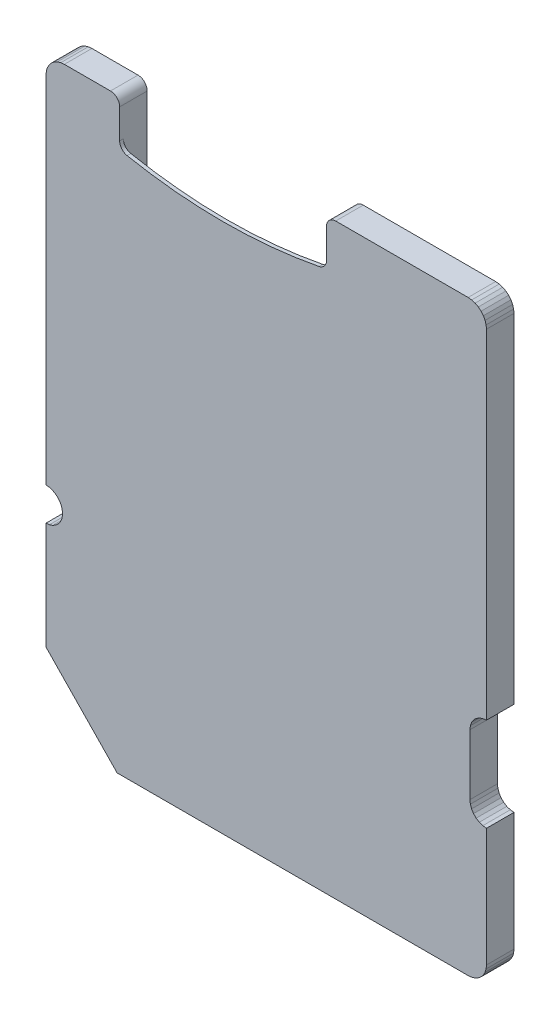
SolidWorks part; units mm, degrees
ref_plane "Ebene vorne" through (0, 0, 0) normal (0, 0, 1) x (1, 0, 0)
ref_plane "Ebene oben" through (0, 0, 0) normal (0, 1, 0) x (1, 0, 0)
ref_plane "Ebene rechts" through (0, 0, 0) normal (1, 0, 0) x (0, 0, -1)
sketch "Skizze1" plane through (0, 0, 0) normal (0, 0, 1) x (1, 0, 0)
  line L201 (121.9951, -56.6192) -> (121.8, -56.6)
  line L202 (121.8, -56.6) -> (99.8, -56.6)
  line L203 (99.8, -56.6) -> (99.6049, -56.6192)
  line L204 (99.6049, -56.6192) -> (99.4173, -56.6761)
  line L205 (99.4173, -56.6761) -> (99.2444, -56.7685)
  line L206 (99.2444, -56.7685) -> (99.0929, -56.8929)
  line L207 (99.0929, -56.8929) -> (98.9685, -57.0444)
  line L208 (98.9685, -57.0444) -> (98.8761, -57.2173)
  line L209 (98.8761, -57.2173) -> (98.8192, -57.4049)
  line L210 (98.8192, -57.4049) -> (98.8, -57.6)
  line L211 (98.8, -57.6) -> (98.8, -76.95)
  line L212 (98.8, -76.95) -> (98.9871, -76.9697)
  line L213 (98.9871, -76.9697) -> (99.1661, -77.0278)
  line L214 (99.1661, -77.0278) -> (99.329, -77.1219)
  line L215 (99.329, -77.1219) -> (99.4688, -77.2478)
  line L216 (99.4688, -77.2478) -> (99.5794, -77.4)
  line L217 (99.5794, -77.4) -> (99.656, -77.5719)
  line L218 (99.656, -77.5719) -> (99.6951, -77.7559)
  line L219 (99.6951, -77.7559) -> (99.6951, -77.9441)
  line L220 (99.6951, -77.9441) -> (99.656, -78.1281)
  line L221 (99.656, -78.1281) -> (99.5794, -78.3)
  line L222 (99.5794, -78.3) -> (99.4688, -78.4522)
  line L223 (99.4688, -78.4522) -> (99.329, -78.5781)
  line L224 (99.329, -78.5781) -> (99.1661, -78.6722)
  line L225 (99.1661, -78.6722) -> (98.9871, -78.7303)
  line L226 (98.9871, -78.7303) -> (98.8, -78.75)
  line L227 (98.8, -78.75) -> (98.8, -84.6)
  line L228 (98.8, -84.6) -> (102.675, -88.6)
  line L229 (102.675, -88.6) -> (121.8, -88.6)
  line L230 (121.8, -88.6) -> (121.9951, -88.5808)
  line L231 (121.9951, -88.5808) -> (122.1827, -88.5239)
  line L232 (122.1827, -88.5239) -> (122.3556, -88.4315)
  line L233 (122.3556, -88.4315) -> (122.5071, -88.3071)
  line L234 (122.5071, -88.3071) -> (122.6315, -88.1556)
  line L235 (122.6315, -88.1556) -> (122.7239, -87.9827)
  line L236 (122.7239, -87.9827) -> (122.7808, -87.7951)
  line L237 (122.7808, -87.7951) -> (122.8, -87.6)
  line L238 (122.8, -87.6) -> (122.8, -81.15)
  line L239 (122.8, -81.15) -> (122.5997, -81.1274)
  line L240 (122.5997, -81.1274) -> (122.4095, -81.0609)
  line L241 (122.4095, -81.0609) -> (122.2389, -80.9536)
  line L242 (122.2389, -80.9536) -> (122.0964, -80.8111)
  line L243 (122.0964, -80.8111) -> (121.9891, -80.6405)
  line L244 (121.9891, -80.6405) -> (121.9226, -80.4503)
  line L245 (121.9226, -80.4503) -> (121.9, -80.25)
  line L246 (121.9, -80.25) -> (121.9, -76.95)
  line L247 (121.9, -76.95) -> (121.9226, -76.7497)
  line L248 (121.9226, -76.7497) -> (121.9891, -76.5595)
  line L249 (121.9891, -76.5595) -> (122.0964, -76.3889)
  line L250 (122.0964, -76.3889) -> (122.2389, -76.2464)
  line L251 (122.2389, -76.2464) -> (122.4095, -76.1391)
  line L252 (122.4095, -76.1391) -> (122.5997, -76.0726)
  line L253 (122.5997, -76.0726) -> (122.8, -76.05)
  line L254 (122.8, -76.05) -> (122.8, -57.6)
  line L255 (122.8, -57.6) -> (122.7808, -57.4049)
  line L256 (122.7808, -57.4049) -> (122.7239, -57.2173)
  line L257 (122.7239, -57.2173) -> (122.6315, -57.0444)
  line L258 (122.6315, -57.0444) -> (122.5071, -56.8929)
  line L259 (122.5071, -56.8929) -> (122.3556, -56.7685)
  line L260 (122.3556, -56.7685) -> (122.1827, -56.6761)
  line L261 (122.1827, -56.6761) -> (121.9951, -56.6192)
  line L262 (121.9951, -56.6192) -> (121.8, -56.6)
  line L263 (121.8, -56.6) -> (99.8, -56.6)
  line L264 (99.8, -56.6) -> (99.6049, -56.6192)
  line L265 (99.6049, -56.6192) -> (99.4173, -56.6761)
  line L266 (99.4173, -56.6761) -> (99.2444, -56.7685)
  line L267 (99.2444, -56.7685) -> (99.0929, -56.8929)
  line L268 (99.0929, -56.8929) -> (98.9685, -57.0444)
  line L269 (98.9685, -57.0444) -> (98.8761, -57.2173)
  line L270 (98.8761, -57.2173) -> (98.8192, -57.4049)
  line L271 (98.8192, -57.4049) -> (98.8, -57.6)
  line L272 (98.8, -57.6) -> (98.8, -76.95)
  line L273 (98.8, -76.95) -> (98.9871, -76.9697)
  line L274 (98.9871, -76.9697) -> (99.1661, -77.0278)
  line L275 (99.1661, -77.0278) -> (99.329, -77.1219)
  line L276 (99.329, -77.1219) -> (99.4688, -77.2478)
  line L277 (99.4688, -77.2478) -> (99.5794, -77.4)
  line L278 (99.5794, -77.4) -> (99.656, -77.5719)
  line L279 (99.656, -77.5719) -> (99.6951, -77.7559)
  line L280 (99.6951, -77.7559) -> (99.6951, -77.9441)
  line L281 (99.6951, -77.9441) -> (99.656, -78.1281)
  line L282 (99.656, -78.1281) -> (99.5794, -78.3)
  line L283 (99.5794, -78.3) -> (99.4688, -78.4522)
  line L284 (99.4688, -78.4522) -> (99.329, -78.5781)
  line L285 (99.329, -78.5781) -> (99.1661, -78.6722)
  line L286 (99.1661, -78.6722) -> (98.9871, -78.7303)
  line L287 (98.9871, -78.7303) -> (98.8, -78.75)
  line L288 (98.8, -78.75) -> (98.8, -84.6)
  line L289 (98.8, -84.6) -> (102.675, -88.6)
  line L290 (102.675, -88.6) -> (121.8, -88.6)
  line L291 (121.8, -88.6) -> (121.9951, -88.5808)
  line L292 (121.9951, -88.5808) -> (122.1827, -88.5239)
  line L293 (122.1827, -88.5239) -> (122.3556, -88.4315)
  line L294 (122.3556, -88.4315) -> (122.5071, -88.3071)
  line L295 (122.5071, -88.3071) -> (122.6315, -88.1556)
  line L296 (122.6315, -88.1556) -> (122.7239, -87.9827)
  line L297 (122.7239, -87.9827) -> (122.7808, -87.7951)
  line L298 (122.7808, -87.7951) -> (122.8, -87.6)
  line L299 (122.8, -87.6) -> (122.8, -81.15)
  line L300 (122.8, -81.15) -> (122.5997, -81.1274)
  line L301 (122.5997, -81.1274) -> (122.4095, -81.0609)
  line L302 (122.4095, -81.0609) -> (122.2389, -80.9536)
  line L303 (122.2389, -80.9536) -> (122.0964, -80.8111)
  line L304 (122.0964, -80.8111) -> (121.9891, -80.6405)
  line L305 (121.9891, -80.6405) -> (121.9226, -80.4503)
  line L306 (121.9226, -80.4503) -> (121.9, -80.25)
  line L307 (121.9, -80.25) -> (121.9, -76.95)
  line L308 (121.9, -76.95) -> (121.9226, -76.7497)
  line L309 (121.9226, -76.7497) -> (121.9891, -76.5595)
  line L310 (121.9891, -76.5595) -> (122.0964, -76.3889)
  line L311 (122.0964, -76.3889) -> (122.2389, -76.2464)
  line L312 (122.2389, -76.2464) -> (122.4095, -76.1391)
  line L313 (122.4095, -76.1391) -> (122.5997, -76.0726)
  line L314 (122.5997, -76.0726) -> (122.8, -76.05)
  line L315 (122.8, -76.05) -> (122.8, -57.6)
  line L316 (122.8, -57.6) -> (122.7808, -57.4049)
  line L317 (122.7808, -57.4049) -> (122.7239, -57.2173)
  line L318 (122.7239, -57.2173) -> (122.6315, -57.0444)
  line L319 (122.6315, -57.0444) -> (122.5071, -56.8929)
  line L320 (122.5071, -56.8929) -> (122.3556, -56.7685)
  line L321 (122.3556, -56.7685) -> (122.1827, -56.6761)
  line L322 (122.1827, -56.6761) -> (121.9951, -56.6192)
  dimension "D1" = 0
extrude "Aufsatz-Linear austragen1" add sketch "Skizze1" along normal blind 1.5 from offset 0.1
sketch "Skizze2" plane through (0, 0, 0) normal (0, 0, 1) x (1, 0, 0)
  line L0 (102.0179, -63.0992) -> (102.0179, -78.3242)
  line L1 (102.0179, -78.3242) -> (105.1468, -78.3242)
  line L2 (105.1468, -78.3242) -> (105.1468, -83.288)
  line L3 (105.1468, -83.288) -> (120.0565, -83.288)
  line L4 (120.0565, -83.288) -> (120.0565, -78.4271)
  line L5 (120.0565, -78.4271) -> (120.8277, -78.4271)
  line L6 (120.8277, -78.4271) -> (120.8277, -75.4255)
  line L7 (120.8277, -75.4255) -> (116.2676, -75.4255)
  line L8 (116.2676, -75.4255) -> (116.2676, -74.2315)
  line L9 (116.2676, -74.2315) -> (118.5543, -74.2315)
  line L10 (118.5543, -74.2315) -> (118.5543, -72.2763)
  line L11 (118.5543, -72.2763) -> (120.6716, -72.2763)
  line L12 (120.6716, -72.2763) -> (120.6716, -62.4012)
  line L13 (120.6716, -62.4012) -> (118.3096, -62.4012)
  line L14 (118.3096, -62.4012) -> (118.3096, -60.5046)
  line L15 (118.3096, -60.5046) -> (115.0611, -60.5046)
  line L16 (115.0611, -60.5046) -> (115.0611, -63.0992)
  line L17 (115.0611, -63.0992) -> (102.0179, -63.0992)
extrude "Schnitt-Linear austragen1" cut sketch "Skizze2" along normal blind 1.2
sketch "Skizze3" plane through (0, 0, 0) normal (0, 0, 1) x (1, 0, 0)
  line L1 (102.0179, -63.0992) -> (115.0611, -63.0992)
  line L2 (102.0179, -63.0992) -> (102.0179, -72.3228)
  line L3 (102.0179, -72.3228) -> (115.0611, -72.3228)
  line L4 (115.0611, -63.0992) -> (115.0611, -72.3228)
extrude "Schnitt-Linear austragen2" cut sketch "Skizze3" along normal blind 1.4
sketch "Skizze4" plane through (0, 0, 0) normal (0, 0, 1) x (1, 0, 0)
  line L1 (102.8139, -55.7807) -> (114.0858, -55.7807)
  line L2 (102.8139, -55.7807) -> (102.8139, -63.7923)
  line L3 (102.8139, -63.7923) -> (114.0858, -63.7923)
  line L4 (114.0858, -55.7807) -> (114.0858, -63.7923)
extrude "Schnitt-Linear austragen3" cut sketch "Skizze4" along normal blind 1.4
sketch "Skizze5" plane through (0, 0, 0) normal (0, 0, 1) x (1, 0, 0)
  line L0 (114.0858, -56.6) -> (114.0858, -59.1156)
  line L1 (114.0858, -63.0992) -> (114.0858, -56.6) construction
  line L2 (114.0858, -56.6) -> (102.8139, -56.6)
  line L3 (102.8139, -56.6) -> (102.8139, -59.1156)
  line L4 (102.8139, -56.6) -> (102.8139, -63.0992) construction
  arc A0 (114.0858, -59.1156) -> (102.8139, -59.1156) centre (108.4498, -32.3811) cw
extrude "Schnitt-Linear austragen4" cut sketch "Skizze5" along normal through all
fillet "Verrundung1" radius 0.5 2 edges at (102.8139, -56.6, 0.85) (114.0858, -56.6, 0.85)
fillet "Verrundung2" radius 0.5 2 edges at (114.0858, -59.1156, 1.5) (102.8139, -59.1156, 1.5)
other "Körper speichern1"
